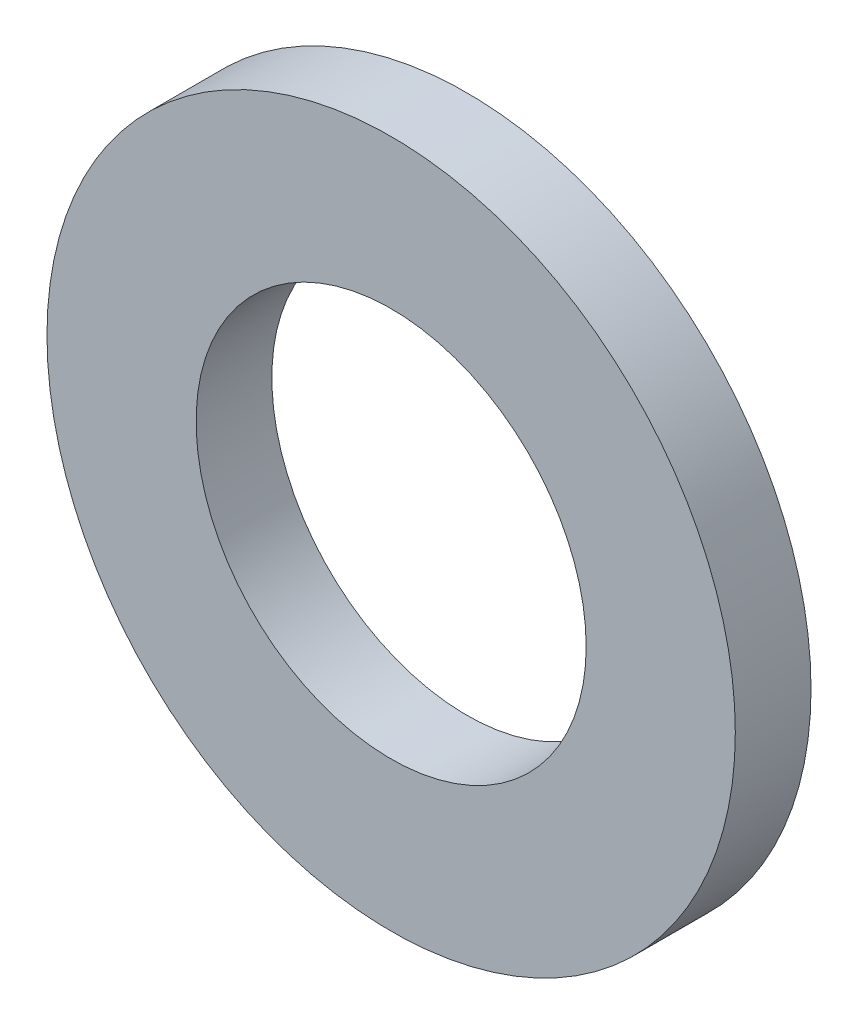
SolidWorks part; units mm, degrees
ref_plane "Front Plane" through (0, 0, 0) normal (0, 0, 1) x (1, 0, 0)
ref_plane "Top Plane" through (0, 0, 0) normal (0, 1, 0) x (1, 0, 0)
ref_plane "Right Plane" through (0, 0, 0) normal (1, 0, 0) x (0, 0, -1)
sketch "Sketch1" plane through (0, 0, 0) normal (0, 0, 1) x (1, 0, 0)
  circle A0 centre (0, 0) radius 15
  circle A1 centre (0, 0) radius 8.5
  dimension "OD" = 30
  dimension "ID1" = 17
extrude "Boss-Extrude1" add sketch "Sketch1" along normal blind 3.3
